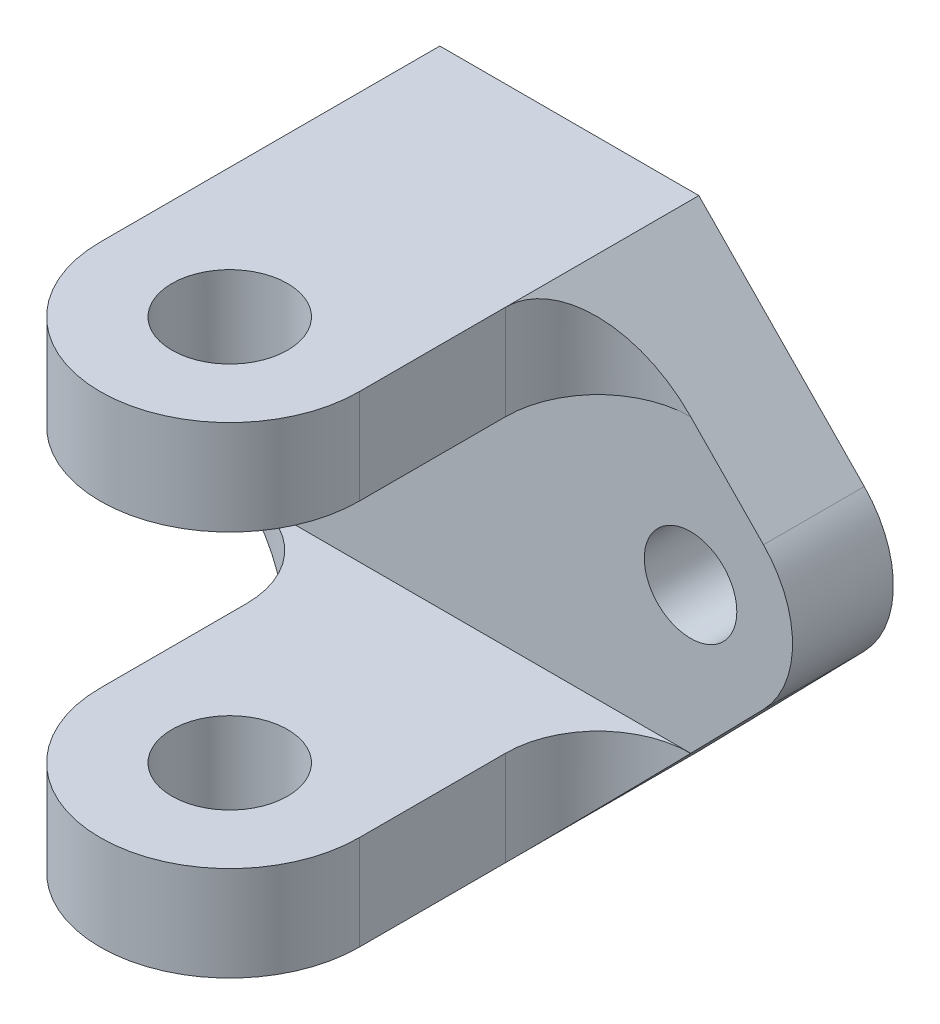
SolidWorks part; units mm, degrees
material "7075-T6 (SN)"
ref_plane "Front Plane" through (0, 0, 0) normal (0, 0, 1) x (1, 0, 0)
ref_plane "Top Plane" through (0, 0, 0) normal (0, 1, 0) x (1, 0, 0)
ref_plane "Right Plane" through (0, 0, 0) normal (1, 0, 0) x (0, 0, -1)
sketch "Sketch1" plane through (0, 0, 0) normal (0, 0, 1) x (1, 0, 0)
  line L0 (15.24, 0) -> (-15.24, 0) construction
  line L1 (-23.24, -16.51) -> (23.24, -16.51)
  line L2 (-23.24, -16.51) -> (-23.24, 16.51)
  line L3 (-23.24, 16.51) -> (23.24, 16.51)
  line L4 (23.24, -16.51) -> (23.24, 16.51)
  line L5 (-23.24, -16.51) -> (23.24, 16.51) construction
  line L6 (-23.24, 16.51) -> (23.24, -16.51) construction
  circle A0 centre (15.24, 0) radius 3.175
  circle A1 centre (-15.24, 0) radius 3.175
  point P0 (0, 0)
  dimension "D1" = 6.35
  dimension "D2" = 30.48
  dimension "D3" = 8
  dimension "D4" = 16.51
extrude "Boss-Extrude1" add sketch "Sketch1" along normal blind 9.46 contours L3 L4 L1 L2
sketch "Sketch2" plane through (0, 0, 9.46) normal (0, 0, 1) x (1, 0, 0)
  line L0 (-15.24, 0) -> (15.24, 0) construction
  line L2 (-23.24, 10) -> (23.24, 10)
  line L3 (-23.24, 10) -> (-23.24, 16.51)
  line L4 (-23.24, 16.51) -> (23.24, 16.51)
  line L5 (23.24, 10) -> (23.24, 16.51)
  line L6 (-23.24, 10) -> (23.24, 16.51) construction
  line L7 (-23.24, 16.51) -> (23.24, 10) construction
  line L8 (-23.24, 16.51) -> (-23.24, -16.51) construction
  line L9 (23.24, -10) -> (23.24, -16.51)
  line L10 (-23.24, -10) -> (-23.24, -16.51)
  line L11 (-23.24, -16.51) -> (23.24, -10) construction
  line L12 (-23.24, -10) -> (23.24, -16.51) construction
  line L13 (-23.24, -10) -> (23.24, -10)
  line L14 (-23.24, -16.51) -> (23.24, -16.51)
  circle A0 centre (-15.24, 0) radius 3.175 construction
  circle A1 centre (15.24, 0) radius 3.175 construction
  point P6 (0, 13.255)
  point P21 (0, -13.255)
  dimension "D1" = 20
extrude "Boss-Extrude2" add sketch "Sketch2" along normal blind 53
sketch "Sketch3" plane through (0, 0, 0) normal (0, 1, 0) x (1, 0, 0)
  point P0 (0, -25.8481)
  dimension "D1" = 25.8481
ref_point "UBJ Point"
sketch "Sketch4" plane through (0, 0, 0) normal (0, 1, 0) x (1, 0, 0)
  circle A0 centre (0, -25.8481) radius 3.9688
  dimension "D1" = 7.9375
extrude "Cut-Extrude1" cut sketch "Sketch4" against normal up to surface and the other way up to surface up to face at (0, -16.51, 31.23) other way up to face at (0, 16.51, 31.23)
sketch "Sketch5" plane through (0, 0, 0) normal (0, 1, 0) x (1, 0, 0)
  line L0 (23.24, -9.46) -> (8.2363, -31.4641)
  line L1 (-8.2363, -31.4641) -> (-23.24, -9.46)
  line L4 (23.24, 0) -> (-23.24, 0)
  line L5 (-23.24, 0) -> (-23.24, -62.46)
  line L6 (-23.24, -62.46) -> (23.24, -62.46)
  line L7 (23.24, -62.46) -> (23.24, 0)
  line L9 (-23.24, -9.46) -> (-23.24, -62.46)
  line L10 (-23.24, -62.46) -> (23.24, -62.46)
  line L11 (23.24, -62.46) -> (23.24, -9.46)
  line L12 (23.24, -9.46) -> (-23.24, -9.46)
  line L13 (23.24, -62.46) -> (23.24, -9.46)
  line L14 (-23.24, -62.46) -> (23.24, -62.46)
  line L15 (-23.24, -9.46) -> (-23.24, -62.46)
  line L17 (23.24, -62.46) -> (23.24, -9.46)
  line L18 (-23.24, -62.46) -> (23.24, -62.46)
  line L19 (-23.24, -9.46) -> (-23.24, -62.46)
  arc A0 (-8.2363, -31.4641) -> (8.2363, -31.4641) centre (0, -25.8481) ccw
  circle A1 centre (0, -25.8481) radius 3.9688 construction
  circle A2 centre (0, -25.8481) radius 3.9688 construction
  dimension "D3" = 6
  dimension "D1" = 0
  dimension "D2" = 0
extrude "Cut-Extrude2" [suppressed] cut sketch "Sketch5" against normal up to surface and the other way up to surface contours A0 L1 L9 L10 L11 L0
sketch "Sketch6" plane through (0, 0, 0) normal (0, 1, 0) x (1, 0, 0)
  line L0 (-8.89, -25.8481) -> (-8.89, -17.46)
  line L1 (8.89, -25.8481) -> (8.89, -17.46)
  line L2 (-16.89, -9.46) -> (-23.24, -9.46)
  line L3 (-8.89, -17.46) -> (-8.89, -9.46)
  line L4 (23.24, -9.46) -> (-23.24, -9.46)
  line L5 (-23.24, -9.46) -> (-23.24, -62.46)
  line L6 (-23.24, -62.46) -> (23.24, -62.46)
  line L7 (23.24, -62.46) -> (23.24, -9.46)
  line L8 (23.24, -9.46) -> (16.89, -9.46)
  line L9 (-23.24, -9.46) -> (-23.24, -62.46)
  line L10 (-23.24, -62.46) -> (23.24, -62.46)
  line L11 (23.24, -62.46) -> (23.24, -9.46)
  line L12 (-8.89, -9.46) -> (-16.89, -9.46)
  line L13 (8.89, -17.46) -> (8.89, -9.46)
  line L14 (8.89, -9.46) -> (16.89, -9.46)
  arc A0 (-8.89, -25.8481) -> (8.89, -25.8481) centre (0, -25.8481) ccw
  circle A1 centre (0, -25.8481) radius 3.9688 construction
  arc A2 (-8.89, -17.46) -> (-16.89, -9.46) centre (-16.89, -17.46) ccw construction
  arc A3 (8.89, -17.46) -> (16.89, -9.46) centre (16.89, -17.46) cw construction
  dimension "D2" = 8.89
  dimension "D3" = 8
  dimension "D1" = 0
extrude "Cut-Extrude3" cut sketch "Sketch6" against normal up to surface and the other way up to surface
fillet "Fillet1" [suppressed] radius 12.7
sketch "Sketch7" plane through (0, 0, 0) normal (0, 0, 1) x (1, 0, 0)
  line L0 (-15.24, 7) -> (-8.89, 7)
  line L1 (-15.24, -7) -> (-8.89, -7)
  line L2 (-8.89, 10) -> (-8.89, 7)
  line L3 (-8.89, -10) -> (-8.89, -7)
  line L4 (0, 10.3988) -> (0, -8.4154) construction
  line L5 (8.89, -10) -> (8.89, -7)
  line L6 (8.89, 10) -> (8.89, 16.51)
  line L7 (23.24, 16.51) -> (23.24, -16.51)
  line L8 (8.89, -10) -> (8.89, -16.51)
  line L9 (8.89, 10) -> (8.89, 7)
  line L10 (15.24, 7) -> (8.89, 7)
  line L11 (15.24, -7) -> (8.89, -7)
  line L12 (8.89, 10) -> (-8.89, 10)
  line L15 (-23.24, 16.51) -> (-23.24, -16.51)
  line L18 (-8.89, -10) -> (8.89, -10)
  line L21 (23.24, -16.51) -> (23.24, 16.51)
  line L27 (-23.24, 16.51) -> (-23.24, -16.51)
  line L33 (23.24, -16.51) -> (23.24, 16.51)
  line L36 (-8.89, 16.51) -> (-8.89, 10)
  line L37 (-8.89, -10) -> (-8.89, -16.51)
  line L48 (-8.89, 10) -> (-8.89, 16.51)
  line L49 (-8.89, -16.51) -> (-8.89, -10)
  line L52 (-8.89, 16.51) -> (-23.24, 16.51)
  line L53 (-8.89, 16.51) -> (-23.24, 16.51)
  line L54 (-23.24, -16.51) -> (-8.89, -16.51)
  line L55 (-23.24, -16.51) -> (-8.89, -16.51)
  line L56 (8.89, -10) -> (8.89, -16.51)
  line L57 (8.89, -16.51) -> (23.24, -16.51)
  line L58 (8.89, -16.51) -> (23.24, -16.51)
  line L59 (23.24, 16.51) -> (8.89, 16.51)
  line L60 (23.24, 16.51) -> (8.89, 16.51)
  line L61 (8.89, 16.51) -> (8.89, 10)
  arc A0 (-15.24, 7) -> (-15.24, -7) centre (-15.24, 0) ccw
  circle A1 centre (-15.24, 0) radius 3.175 construction
  arc A2 (15.24, 7) -> (15.24, -7) centre (15.24, 0) cw
  dimension "D2" = 7
  dimension "D1" = 0
extrude "Cut-Extrude4" cut sketch "Sketch7" along normal up to surface (9.46 mm away)
fillet "Fillet2" [suppressed] radius 5
sketch "Sketch8" plane through (0, 0, 0) normal (0, 0, 1) x (1, 0, 0)
  line L0 (15.24, 7) -> (8.89, 7) construction
  line L1 (8.89, 16.51) -> (8.89, 7) construction
  line L2 (15.24, 7) -> (8.89, 7)
  line L3 (8.89, 16.51) -> (8.89, 7)
  line L4 (6.7586, 0) -> (-5.803, 0) construction
  line L5 (0, 7.1591) -> (0, -7.1591) construction
  line L6 (8.89, 16.51) -> (20.2457, 4.8932)
  line L7 (-8.89, 16.51) -> (-8.89, 7)
  line L8 (-15.24, 7) -> (-8.89, 7)
  line L9 (-8.89, 16.51) -> (-20.2457, 4.8932)
  line L10 (-8.89, -16.51) -> (-20.2457, -4.8932)
  line L11 (-15.24, -7) -> (-8.89, -7)
  line L12 (-8.89, -16.51) -> (-8.89, -7)
  line L13 (8.89, -16.51) -> (8.89, -7)
  line L14 (15.24, -7) -> (8.89, -7)
  line L15 (8.89, -16.51) -> (20.2457, -4.8932)
  arc A0 (15.24, -7) -> (15.24, 7) centre (15.24, 0) ccw construction
  arc A1 (20.2457, 4.8932) -> (15.24, 7) centre (15.24, 0) ccw
  arc A2 (-20.2457, 4.8932) -> (-15.24, 7) centre (-15.24, 0) cw
  arc A3 (-20.2457, -4.8932) -> (-15.24, -7) centre (-15.24, 0) ccw
  arc A4 (20.2457, -4.8932) -> (15.24, -7) centre (15.24, 0) cw
extrude "Boss-Extrude3" add sketch "Sketch8" along normal up to surface (9.46 mm away) contours L15 A4 L14 L13 | A3 L10 L12 L11 | L6 A1 L2 L3 | L9 A2 L8 L7 up to face at (0, 0, 9.46)
fillet "Fillet3" radius 6.35 4 edges at (8.89, 13.255, 9.46) (-8.89, 13.255, 9.46) (-8.89, -13.255, 9.46) (8.89, -13.255, 9.46)
sketch "Sketch10" plane through (0, 0, 0) normal (0, 0, 1) x (1, 0, 0)
  line L5 (-8.89, 16.51) -> (-20.2457, 4.8932)
  line L6 (-8.89, 16.51) -> (-20.2457, 4.8932)
  line L7 (8.89, 16.51) -> (-8.89, 16.51)
  line L8 (20.2457, 4.8932) -> (8.89, 16.51)
  line L9 (8.89, -16.51) -> (20.2457, -4.8932)
  line L10 (-8.89, -16.51) -> (8.89, -16.51)
  line L13 (8.89, 16.51) -> (-8.89, 16.51)
  line L14 (20.2457, 4.8932) -> (8.89, 16.51)
  line L15 (8.89, -16.51) -> (20.2457, -4.8932)
  line L16 (-8.89, -16.51) -> (8.89, -16.51)
  line L18 (-20.2457, -4.8932) -> (-8.89, -16.51)
  line L19 (-20.2457, -4.8932) -> (-8.89, -16.51)
  arc A2 (-20.2457, 4.8932) -> (-20.2457, -4.8932) centre (-15.24, 0) ccw
  arc A3 (20.2457, -4.8932) -> (20.2457, 4.8932) centre (15.24, 0) ccw
  arc A5 (20.2457, -4.8932) -> (20.2457, 4.8932) centre (15.24, 0) ccw
  arc A6 (-20.2457, 4.8932) -> (-20.2457, -4.8932) centre (-15.24, 0) ccw
  dimension "D1" = 0
extrude "Cut-Extrude5" cut sketch "Sketch10" along normal blind 2.54
